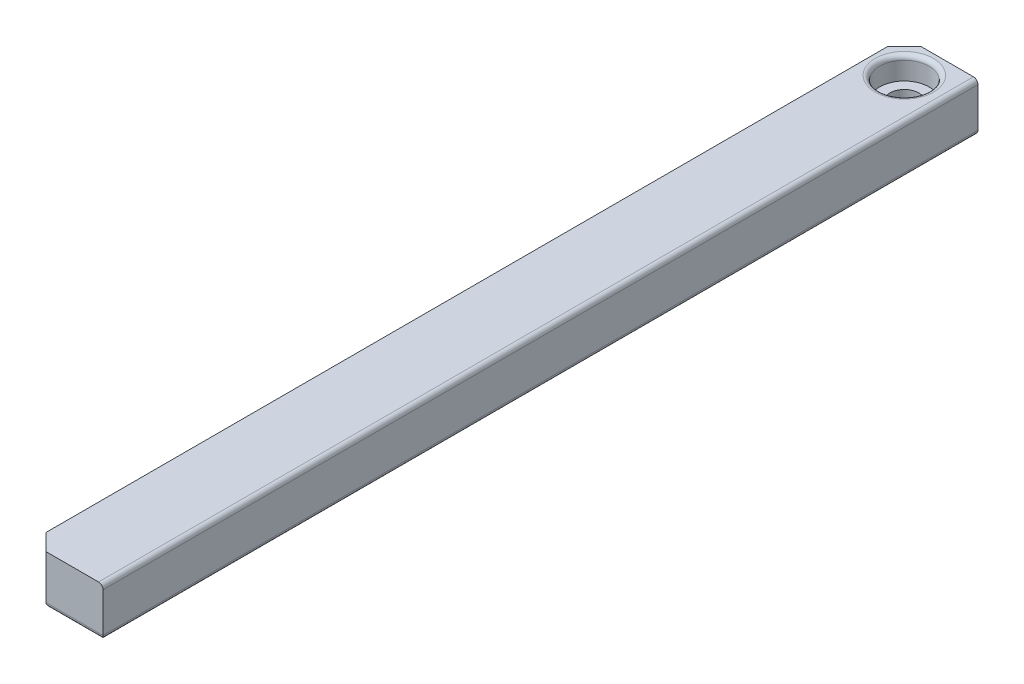
SolidWorks part; units mm, degrees
ref_plane "前视基准面" through (0, 0, 0) normal (0, 0, 1) x (1, 0, 0)
ref_plane "上视基准面" through (0, 0, 0) normal (0, 1, 0) x (1, 0, 0)
ref_plane "右视基准面" through (0, 0, 0) normal (1, 0, 0) x (0, 0, -1)
other "Configuration Table"
sketch "草图1" plane through (0, 0, 0) normal (0, 1, 0) x (1, 0, 0)
  line L0 (21.7593, 0) -> (29.9593, 0)
  line L1 (29.9593, 0) -> (29.9593, 97.4)
  line L2 (29.9593, 97.4) -> (21.7593, 97.4)
  line L3 (21.7593, 97.4) -> (21.7593, 0)
extrude "凸台-拉伸1" add sketch "草图1" along normal blind 5.4
sketch "草图2" plane through (0, 5.4, 0) normal (0, 1, 0) x (1, 0, 0)
  line L0 (21.7593, 97.4) -> (23.6093, 97.4)
  line L1 (29.9593, 97.4) -> (21.7593, 97.4) construction
  line L2 (21.7593, 97.4) -> (21.7593, 95.55)
  line L3 (21.7593, 97.4) -> (21.7593, 0) construction
  line L4 (21.7593, 95.55) -> (23.6093, 97.4)
  line L5 (21.7593, 0) -> (23.6093, 0)
  line L6 (21.7593, 0) -> (29.9593, 0) construction
  line L7 (21.7593, 0) -> (21.7593, 1.85)
  line L8 (21.7593, 1.85) -> (23.6093, 0)
  circle A0 centre (25.4593, 93.7) radius 1.6
extrude "切除-拉伸1" cut sketch "草图2" against normal through all
fillet "圆角1" radius 0.5 7 edges at (22.6843, 0, -0.925) (26.7843, 0, 0) (29.9593, 0, -48.7) (26.7843, 0, -97.4) (22.6843, 0, -96.475) (21.7593, 0, -48.7) (25.4593, 0, -92.1)
fillet "圆角2" radius 0.5 1 edges at (29.9593, 5.4, -48.7)
sketch "草图3" plane through (0, 5.4, 0) normal (0, 1, 0) x (1, 0, 0)
  circle A0 centre (25.4593, 93.7) radius 2.75
extrude "切除-拉伸2" cut sketch "草图3" against normal blind 2.5
fillet "圆角3" radius 0.5 1 edges at (25.4593, 5.4, -90.95)
